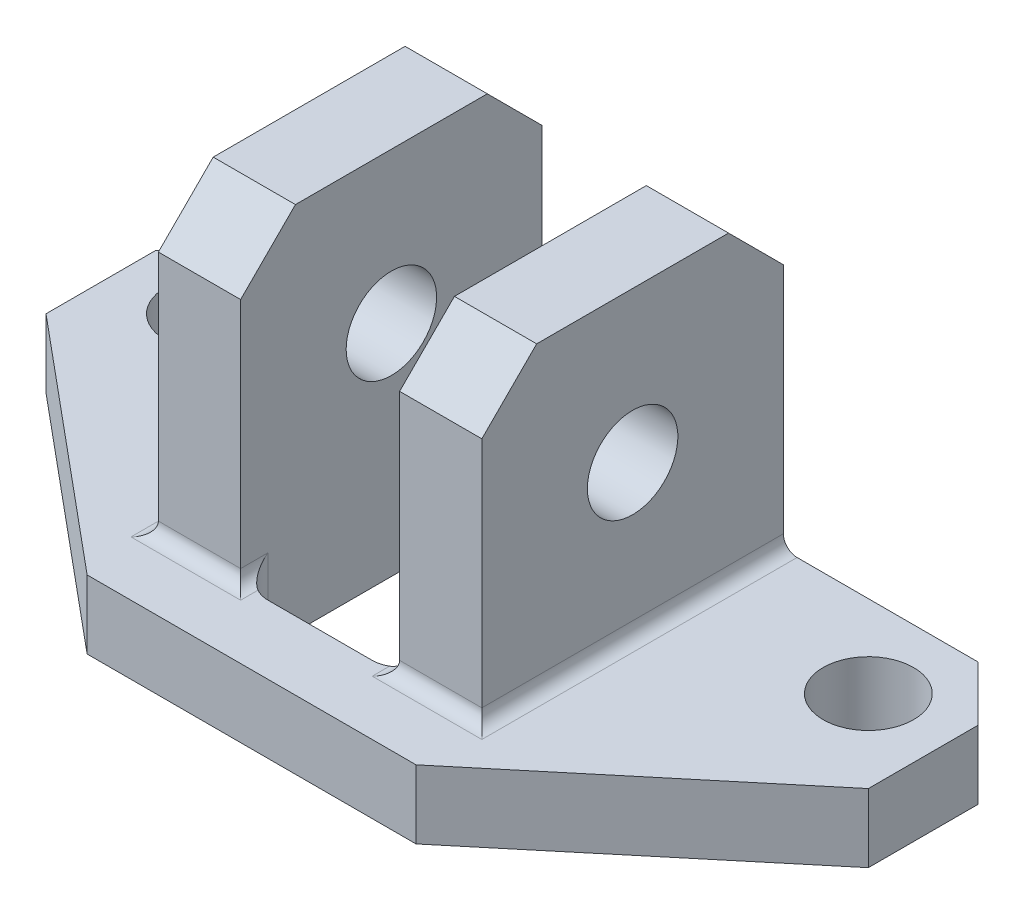
SolidWorks part; units mm, degrees
ref_plane "前视基准面" through (0, 0, 0) normal (0, 0, 1) x (1, 0, 0)
ref_plane "上视基准面" through (0, 0, 0) normal (0, 1, 0) x (1, 0, 0)
ref_plane "右视基准面" through (0, 0, 0) normal (1, 0, 0) x (0, 0, -1)
sketch "草图1" plane through (0, 0, 0) normal (0, 1, 0) x (1, 0, 0)
  line L1 (-15, 8) -> (15, 8)
  line L2 (-15, 8) -> (-15, -8)
  line L3 (-15, -8) -> (15, -8)
  line L4 (15, 8) -> (15, -8)
  line L5 (-15, 8) -> (15, -8) construction
  line L6 (-15, -8) -> (15, 8) construction
  point P0 (0, 0)
  dimension "D1" = 30
  dimension "D2" = 16
extrude "凸台-拉伸1" add sketch "草图1" along normal blind 2.5
sketch "草图3" plane through (0, 2.5, 0) normal (0, 1, 0) x (1, 0, 0)
  line L0 (0, 8) -> (0, -8) construction
  line L1 (-12, 5) -> (12, 5) construction
  line L2 (-12, 5) -> (-12, -5) construction
  line L3 (-12, -5) -> (12, -5) construction
  line L4 (12, 5) -> (12, -5) construction
  line L5 (-12, 5) -> (12, -5) construction
  line L6 (-12, -5) -> (12, 5) construction
  line L7 (15, 8) -> (-15, 8) construction
  line L8 (-15, -8) -> (15, -8) construction
  line L9 (-15, 0) -> (15, 0) construction
  line L10 (-15, 8) -> (-15, -8) construction
  line L11 (15, -8) -> (15, 8) construction
  circle A0 centre (-12, 5) radius 1.65
  circle A1 centre (12, 5) radius 1.65
  circle A2 centre (12, -5) radius 1.65
  circle A3 centre (-12, -5) radius 1.65
  circle A4 centre (0, 5) radius 1.65
  circle A6 centre (0, -5) radius 1.65 [skipped]
  point P0 (0, 0)
  dimension "D3" = 3.3
  dimension "D1" = 24
  dimension "D2" = 10
  dimension "D4" = 2
extrude "切除-拉伸1" cut sketch "草图3" against normal blind 2.5
sketch "草图4" plane through (0, 2.5, 0) normal (0, 1, 0) x (1, 0, 0)
  line L0 (0, 8) -> (0, -8) construction
  line L1 (15, 8) -> (-15, 8) construction
  line L2 (-15, -8) -> (15, -8) construction
  line L4 (-2.9, 8) -> (2.9, 8)
  line L5 (-2.9, 8) -> (-2.9, -3)
  line L6 (-2.9, -3) -> (2.9, -3)
  line L7 (2.9, 8) -> (2.9, -3)
  dimension "D1" = 5.8
  dimension "D2" = 11
extrude "切除-拉伸2" cut sketch "草图4" against normal blind 2.5
sketch "草图5" plane through (0, 2.5, 0) normal (0, 1, 0) x (1, 0, 0)
  line L0 (0, 0) -> (0, -8) construction
  line L1 (-15, -8) -> (15, -8) construction
  line L2 (-2.9, -3) -> (2.9, -3) construction
  line L3 (-2.9, 8) -> (-5.9, 8)
  line L4 (-2.9, 8) -> (-2.9, -3)
  line L5 (-2.9, -3) -> (-5.9, -3)
  line L6 (-5.9, 8) -> (-5.9, -3)
  line L7 (2.9, -3) -> (5.9, -3)
  line L8 (5.9, 8) -> (5.9, -3)
  line L9 (2.9, 8) -> (5.9, 8)
  line L10 (2.9, 8) -> (2.9, -3)
  dimension "D1" = 3
extrude "凸台-拉伸2" add sketch "草图5" along normal blind 11
sketch "草图6" plane through (-5.9, 0, 0) normal (-1, 0, 0) x (0, 0, 1)
  line L1 (-8, 13.5) -> (3, 13.5) construction
  line L2 (-8, 13.5) -> (-8, 2.5) construction
  line L3 (-8, 2.5) -> (3, 2.5) construction
  line L4 (3, 13.5) -> (3, 2.5) construction
  line L5 (-8, 13.5) -> (3, 2.5) construction
  line L6 (-8, 2.5) -> (3, 13.5) construction
  line L7 (-8, 13.5) -> (-8, 2.5) construction
  line L8 (-8, 13.5) -> (3, 13.5) construction
  line L9 (3, 13.5) -> (3, 2.5) construction
  circle A0 centre (-2.5, 8) radius 1.65
  point P0 (-2.5, 8)
  dimension "D1" = 3.3
extrude "切除-拉伸3" cut sketch "草图6" against normal through all
sketch "草图7" plane through (0, 2.5, 0) normal (0, 1, 0) x (1, 0, 0)
  line L0 (-15, 2) -> (-3, -8)
  line L1 (-15, 8) -> (-15, -8) construction
  line L2 (-15, -8) -> (15, -8) construction
  line L3 (-3, -8) -> (-15, -8)
  line L4 (-15, -8) -> (-15, 2)
  line L5 (0, -8) -> (0, -3) construction
  line L6 (-2.9, -3) -> (2.9, -3) construction
  line L7 (-5.9, 8) -> (-15, 8) construction
  line L8 (3, -8) -> (15, -8)
  line L9 (15, 2) -> (3, -8)
  line L10 (15, -8) -> (15, 2)
  dimension "D1" = 6
  dimension "D2" = 3
extrude "切除-拉伸4" cut sketch "草图7" against normal through all
chamfer "倒角1" distance 2 angle 45 6 edges at (-4.4, 13.5, -8) (-4.4, 13.5, 3) (4.4, 13.5, 3) (4.4, 13.5, -8) (-15, 1.25, -8) (15, 1.25, -8)
fillet "圆角1" radius 1 2 edges at (-2.9, 1.25, 3) (2.9, 1.25, 3)
fillet "圆角2" radius 0.5 6 edges at (5.9, 2.5, -2.5) (-5.9, 2.5, -2.5) (-2.9, 2.5, 2.5) (-4.4, 2.5, 3) (4.4, 2.5, 3) (2.9, 2.5, 2.5)
sketch "草图8" plane through (0, 2.5, 0) normal (0, 1, 0) x (1, 0, 0)
  line L0 (-6, -5.5) -> (6, -5.5)
  line L1 (-3, -8) -> (-15, 2) construction
  line L3 (6, -5.5) -> (3, -8)
  line L4 (3, -8) -> (-3, -8)
  line L5 (-3, -8) -> (-6, -5.5)
  line L6 (-1.9, -3) -> (1.9, -3) construction
  line L8 (15, 2) -> (3, -8) construction
  dimension "D1" = 2.5
extrude "切除-拉伸6" cut sketch "草图8" against normal through all
